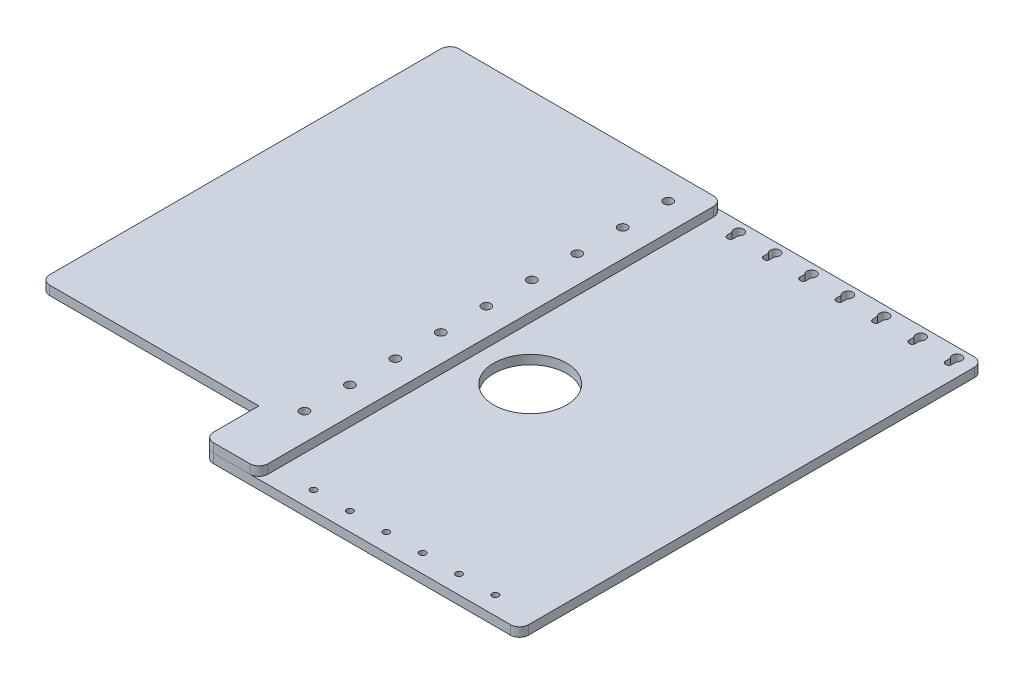
SolidWorks part; units mm, degrees
ref_plane "Front Plane" through (0, 0, 0) normal (0, 0, 1) x (1, 0, 0)
ref_plane "Top Plane" through (0, 0, 0) normal (0, 1, 0) x (1, 0, 0)
ref_plane "Right Plane" through (0, 0, 0) normal (1, 0, 0) x (0, 0, -1)
sketch "Sketch1" plane through (0, 0, 0) normal (0, 1, 0) x (1, 0, 0)
  line L1 (-86.635, -127.5) -> (86.635, -127.5)
  line L2 (-86.635, -127.5) -> (-86.635, 127.5)
  line L3 (-86.635, 127.5) -> (86.635, 127.5)
  line L4 (86.635, -127.5) -> (86.635, 127.5)
  line L5 (-86.635, -127.5) -> (86.635, 127.5) construction
  line L6 (-86.635, 127.5) -> (86.635, -127.5) construction
  circle A0 centre (-27.5, -7.5) radius 20
  point P0 (0, 0)
  point P13 (-12.7083, 23.4551)
  dimension "D5" = 120
  dimension "D7" = 40
  dimension "D1" = 255
  dimension "D2" = 173.27
  dimension "D6" = 114.135
extrude "Plate body" add sketch "Sketch1" along normal blind 5
sketch "Sketch2" plane through (0, 5, 0) normal (0, 1, 0) x (1, 0, 0)
  line L0 (-86.635, 127.5) -> (-206.635, 127.5)
  line L1 (-206.635, 127.5) -> (-206.635, -97.5)
  line L2 (-206.635, -97.5) -> (-86.635, -97.5)
  line L3 (-86.635, -127.5) -> (-86.635, 127.5) construction
  line L4 (-86.635, -97.5) -> (-86.635, 127.5)
  line L5 (-86.635, -127.5) -> (86.635, -127.5) construction
  line L6 (-86.635, 127.5) -> (-56.635, 127.5)
  line L7 (-86.635, 127.5) -> (86.635, 127.5) construction
  line L8 (-56.635, 127.5) -> (-56.635, -127.5)
  line L9 (-56.635, -127.5) -> (-86.635, -127.5)
  line L10 (-86.635, -127.5) -> (-86.635, -97.5)
  dimension "D1" = 120
  dimension "D2" = 30
  dimension "D3" = 30
extrude "Extension" add sketch "Sketch2" along normal blind 5 separate body
sketch "Sketch8" plane through (0, 10, 0) normal (0, 1, 0) x (1, 0, 0)
  line L0 (-71.635, 127.5) -> (-71.635, 112.5) construction
  line L1 (-86.635, 127.5) -> (-56.635, 127.5) construction
  line L2 (-71.635, 112.5) -> (-71.635, 87.5) construction
  circle A0 centre (-71.635, 112.5) radius 2.5
  circle A1 centre (-71.635, 87.5) radius 2.5
  circle A2 centre (-71.635, 62.5) radius 2.5
  circle A3 centre (-71.635, 37.5) radius 2.5
  circle A4 centre (-71.635, 12.5) radius 2.5
  circle A5 centre (-71.635, -12.5) radius 2.5
  circle A6 centre (-71.635, -37.5) radius 2.5
  circle A7 centre (-71.635, -62.5) radius 2.5
  circle A8 centre (-71.635, -87.5) radius 2.5
  circle A9 centre (-71.635, -112.5) radius 2.5 construction
  point P1 (-71.635, 112.5)
  point P11 (-71.635, 87.5)
  point P13 (-71.635, 62.5)
  point P15 (-71.635, 37.5)
  point P17 (-71.635, 12.5)
  point P19 (-71.635, -12.5)
  point P21 (-71.635, -37.5)
  point P23 (-71.635, -62.5)
  point P25 (-71.635, -87.5)
  point P27 (-71.635, -112.5)
  dimension "D2" = 5
  dimension "D1" = 15
  dimension "D3" = 25
  dimension "D4" = 10
extrude "Extension connector" cut sketch "Sketch8" against normal up to surface (10 mm away)
sketch "T-slot mapping" plane through (0, 0, 0) normal (0, 1, 0) x (1, 0, 0)
  line L0 (-206.635, 127.5) -> (-206.635, -97.5) construction
  line L1 (-206.635, 125) -> (86.635, 125) construction
  line L2 (-206.635, 125) -> (-206.635, 110) construction
  line L3 (-206.635, 110) -> (86.635, 110) construction
  line L4 (86.635, 125) -> (86.635, 110) construction
  line L5 (86.635, -127.5) -> (86.635, 127.5) construction
  line L6 (-86.635, 127.5) -> (86.635, 127.5) construction
  line L7 (86.635, 117.5) -> (-206.635, 117.5) construction
  line L8 (-206.635, 119.5) -> (86.635, 119.5) construction
  line L9 (-206.635, 119.5) -> (-206.635, 115.5) construction
  line L10 (-206.635, 115.5) -> (86.635, 115.5) construction
  line L11 (86.635, 119.5) -> (86.635, 115.5) construction
  dimension "D1" = 2.5
  dimension "D2" = 15
  dimension "D3" = 4
  dimension "D4" = 5.5
sketch "Sketch15" plane through (0, 0, 0) normal (0, 1, 0) x (1, 0, 0)
  line L0 (86.635, 117.5) -> (-206.635, 117.5) construction
  line L1 (75.735, 116) -> (79.135, 116)
  line L2 (75.735, 116) -> (75.735, 120.25)
  line L3 (75.735, 120.25) -> (79.135, 120.25)
  line L4 (79.135, 116) -> (79.135, 120.25)
  line L5 (75.735, 116) -> (79.135, 120.25) construction
  line L6 (75.735, 120.25) -> (79.135, 116) construction
  circle A1 centre (77.435, 122.2502) radius 2.625
  point P2 (77.435, 118.125)
  point P5 (77.435, 119.6252)
  point P8 (0, 0)
  point P9 (0, 0)
  point P13 (0, 0)
  dimension "D1" = 5.25
  dimension "D2" = 4.25
  dimension "D3" = 3.4
  dimension "D4" = 7.5
  dimension "D5" = 1.5
extrude "Keyhole slot base" cut sketch "Sketch15" along normal up to surface (5 mm away) contours A1 | L4 L3 L2 L1 up to face at (-71.635, 5, -110)
fillet "Keyhole" radius 1.5 2 edges at (79.135, 2.5, -116) (75.735, 2.5, -116)
pattern_linear "LPattern1 keyhole slots" count 7 spacing 20 along (-1, 0, 0) of "Keyhole slot base", "Keyhole"
sketch "Sketch16" plane through (0, 5, 0) normal (0, 1, 0) x (1, 0, 0)
  line L0 (-86.635, -127.5) -> (86.635, -127.5) construction
  line L1 (-86.635, -97.5) -> (-86.635, -127.5) construction
  line L2 (-76.635, -117.5) -> (-56.635, -117.5) construction
  circle A0 centre (-76.635, -117.5) radius 1.725 construction
  circle A1 centre (-56.635, -117.5) radius 1.725 construction
  circle A2 centre (-36.635, -117.5) radius 1.725
  circle A3 centre (-16.635, -117.5) radius 1.725
  circle A4 centre (3.365, -117.5) radius 1.725
  circle A5 centre (23.365, -117.5) radius 1.725
  circle A6 centre (43.365, -117.5) radius 1.725
  circle A7 centre (63.365, -117.5) radius 1.725
  point P7 (0, 0)
  dimension "D1" = 3.45
  dimension "D2" = 10
  dimension "D3" = 10
  dimension "D4" = 20
  dimension "D5" = 8
extrude "Front mounting points" cut sketch "Sketch16" against normal up to surface (5 mm away) up to face at (77.435, 0, -118.584)
fillet "Plate body fillet" radius 5 4 edges at (-86.635, 2.5, 127.5) (-86.635, 2.5, -127.5) (86.635, 2.5, -127.5) (86.635, 2.5, 127.5)
fillet "Extension fillet" radius 5 5 edges at (-56.635, 7.5, 127.5) (-56.635, 7.5, -127.5) (-206.635, 7.5, -127.5) (-206.635, 7.5, 97.5) (-86.635, 7.5, 127.5)
